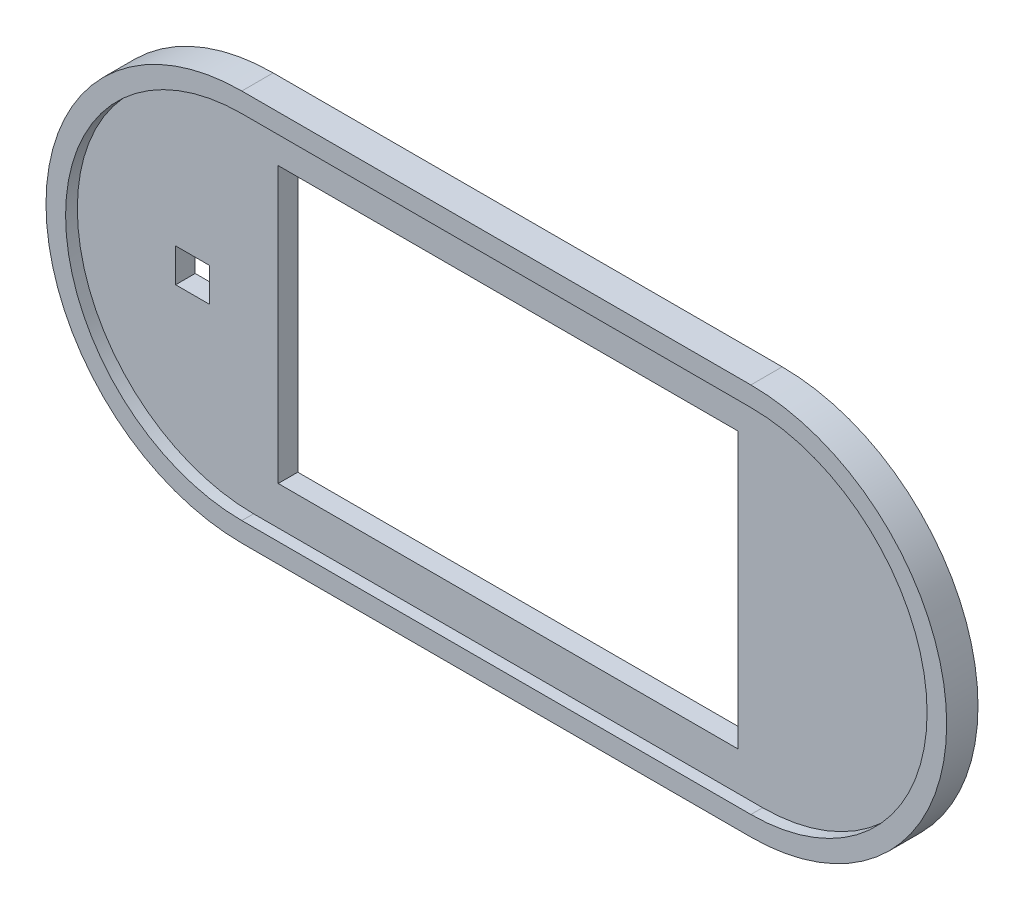
SolidWorks part; units mm, degrees
ref_plane "Front Plane" through (0, 0, 0) normal (0, 0, 1) x (1, 0, 0)
ref_plane "Top Plane" through (0, 0, 0) normal (0, 1, 0) x (1, 0, 0)
ref_plane "Right Plane" through (0, 0, 0) normal (1, 0, 0) x (0, 0, -1)
sketch "Sketch1" plane through (0, 0, 0) normal (0, 0, 1) x (1, 0, 0)
  line L1 (0, 0) -> (-130, 0)
  line L3 (0, -100) -> (-130, -100)
  arc A0 (-130, 0) -> (-130, -100) centre (-130, -50) ccw
  arc A1 (0, 0) -> (0, -100) centre (0, -50) cw
  dimension "D1" = 100
  dimension "D2" = 130
extrude "Boss-Extrude1" add sketch "Sketch1" along normal blind 8
shell "Shell1" thickness 5
sketch "Sketch2" plane through (0, 0, 0) normal (0, 0, -1) x (-1, 0, 0)
  line L0 (65, 0) -> (65, -100) construction
  line L1 (0, 0) -> (130, 0) construction
  line L2 (130, -100) -> (0, -100) construction
  line L3 (145.5961, -50) -> (-15.5961, -50) construction
  line L4 (6.3, -85.15) -> (123.7, -85.15)
  line L5 (6.3, -85.15) -> (6.3, -14.85)
  line L6 (6.3, -14.85) -> (123.7, -14.85)
  line L7 (123.7, -85.15) -> (123.7, -14.85)
  line L8 (6.3, -85.15) -> (123.7, -14.85) construction
  line L9 (6.3, -14.85) -> (123.7, -85.15) construction
  line L11 (141.2961, -45.7) -> (149.8961, -45.7)
  line L12 (141.2961, -45.7) -> (141.2961, -54.3)
  line L13 (141.2961, -54.3) -> (149.8961, -54.3)
  line L14 (149.8961, -45.7) -> (149.8961, -54.3)
  line L15 (141.2961, -45.7) -> (149.8961, -54.3) construction
  line L16 (141.2961, -54.3) -> (149.8961, -45.7) construction
  point P6 (65, -50)
  point P11 (145.5961, -50)
  point P14 (65, -50)
  dimension "D1" = 117.4
  dimension "D2" = 70.3
  dimension "D3" = 8.6
extrude "Cut-Extrude1" cut sketch "Sketch2" against normal blind 5
sketch "Sketch3" plane through (0, 0, 5) normal (0, 0, 1) x (1, 0, 0)
  line L0 (-123.7, -14.85) -> (-123.7, -85.15) construction
  line L1 (-125.1, -12.4055) -> (-4.3, -12.4055)
  line L6 (-125.1, -12.4055) -> (-125.1, -88.3055)
  line L7 (-125.1, -88.3055) -> (-4.3, -88.3055)
  line L8 (-4.3, -12.4055) -> (-4.3, -88.3055)
  line L10 (-6.3, -85.15) -> (-6.3, -14.85) construction
  dimension "D1" = 75.9
  dimension "D2" = 120.8
  dimension "D3" = 1.4
